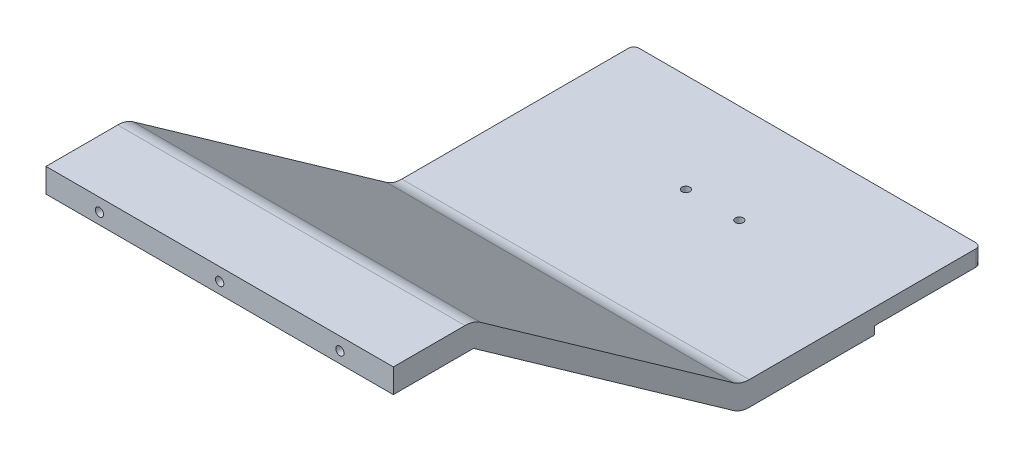
SolidWorks part; units mm, degrees
ref_plane "前视基准面" through (0, 0, 0) normal (0, 0, 1) x (1, 0, 0)
ref_plane "上视基准面" through (0, 0, 0) normal (0, 1, 0) x (1, 0, 0)
ref_plane "右视基准面" through (0, 0, 0) normal (1, 0, 0) x (0, 0, -1)
other "Configuration Table"
sketch "草图1" plane through (0, 0, 0) normal (0, 0, 1) x (1, 0, 0)
  line L0 (0, 0) -> (0, 79)
  line L1 (0, 79) -> (79, 79)
  line L2 (79, 79) -> (79, 70)
  line L3 (79, 70) -> (9, 70)
  line L4 (9, 70) -> (9, 0)
  line L5 (9, 0) -> (0, 0)
  dimension "D1" = 9
  dimension "D2" = 9
  dimension "D3" = 70
  dimension "D4" = 70
ref_plane "基准面1" through (0, 0, 100) normal (0, 0, 1) x (1, 0, 0)
sketch "草图2" plane through (0, 0, 100) normal (0, 0, 1) x (1, 0, 0)
  line L0 (0, 79) -> (-70.7107, 149.7107) construction
  line L1 (0, 0) -> (0, 79) construction
  line L2 (-70.7107, 149.7107) -> (-70.7107, 0)
  line L3 (-70.7107, 0) -> (-61.7107, 0)
  line L4 (-61.7107, 0) -> (-61.7107, 140.7107)
  line L5 (-61.7107, 140.7107) -> (79, 140.7107)
  line L6 (79, 140.7107) -> (79, 149.7107)
  line L7 (79, 149.7107) -> (-70.7107, 149.7107)
  line L8 (0, 0) -> (0, 79) construction
  line L9 (0, 79) -> (79, 79) construction
  dimension "D1" = 135
  dimension "D2" = 9
  dimension "D3" = 100
  dimension "D4" = 79
loft "放样1" add profiles "草图1", "草图2"
sketch "草图4" plane through (0, 0, 0) normal (0, 0, -1) x (-1, 0, 0)
  line L7 (-9, 0) -> (0, 0)
  line L8 (0, 0) -> (0, 79)
  line L9 (0, 79) -> (-79, 79)
  line L10 (-79, 79) -> (-79, 70)
  line L11 (-79, 70) -> (-77.7656, 70)
  line L12 (-77.7656, 70) -> (-9, 70)
  line L13 (-9, 70) -> (-9, 0)
  line L14 (-9, 0) -> (0, 0)
  line L15 (0, 0) -> (0, 79)
  line L16 (0, 79) -> (-79, 79)
  line L17 (-79, 79) -> (-79, 70)
  line L18 (-79, 70) -> (-77.7656, 70)
  line L19 (-77.7656, 70) -> (-9, 70)
  line L20 (-9, 70) -> (-9, 0)
  dimension "D1" = 0
extrude "凸台-拉伸1" add sketch "草图4" along normal blind 50
sketch "草图9" plane through (0, 0, -50) normal (0, 0, -1) x (-1, 0, 0)
  line L0 (-9, 70) -> (-9, 0) construction
  line L1 (-9, 70) -> (-55, 70)
  line L2 (-9, 70) -> (-9, 30)
  line L3 (-15, 64) -> (-55, 64)
  line L4 (-55, 70) -> (-55, 64)
  line L6 (-15, 64) -> (-15, 30)
  line L7 (-15, 30) -> (-9, 30)
  dimension "D1" = 6
  dimension "D2" = 46
  dimension "D3" = 6
  dimension "D4" = 40
extrude "凸台-拉伸3" add sketch "草图9" against normal blind 6
fillet "圆角1" radius 10 7 edges
sketch "草图11" plane through (0, 0, -44) normal (0, 0, 1) x (1, 0, 0)
  circle A0 centre (12, 45) radius 1.55
  circle A1 centre (12, 65) radius 1.55
  circle A2 centre (30, 67) radius 1.55
  circle A3 centre (50, 67) radius 1.55
  dimension "D1" = 3.1
extrude "切除-拉伸1" cut sketch "草图11" against normal through all
sketch "草图12" plane through (0, 0, -50) normal (0, 0, -1) x (-1, 0, 0)
  line L0 (0, 19) -> (0, 0)
  line L1 (0, 0) -> (0, 69) construction
  line L2 (0, 0) -> (-6, 0)
  line L3 (-9, 0) -> (0, 0) construction
  line L5 (-6, 0) -> (-6, 19)
  line L6 (0, 19) -> (-6, 19)
  line L7 (-2.9289, 76.0711) -> (-93.7798, -14.7798) construction
  line L8 (0, 0) -> (0, 69) construction
  line L9 (-60, 79) -> (-60, 73)
  line L10 (-79, 73) -> (-60, 73)
  line L11 (-79, 79) -> (-79, 73)
  line L12 (-60, 79) -> (-79, 79)
  arc A0 (0, 69) -> (-10, 79) centre (-10, 69) ccw construction
  dimension "D1" = 19
  dimension "D2" = 6
  dimension "D3" = 45
extrude "凸台-拉伸4" add sketch "草图12" along normal blind 40
fillet "圆角2" radius 2 9 edges at (3, 0, -90) (3, 19, -90) (9, 30, -47) (15, 30, -47) (15, 64, -47) (55, 70, -47) (55, 64, -47) (79, 76, -90) (60, 76, -90)
sketch "草图13" plane through (79, 0, 0) normal (1, 0, 0) x (0, 0, -1)
  line L0 (90, 79) -> (88, 79) construction
  line L1 (90, 79) -> (90, 73) construction
  line L9 (50, 73) -> (88, 73)
  line L10 (88, 73) -> (88, 79)
  line L11 (88, 79) -> (3.1784, 79)
  line L12 (-2.5951, 80.835) -> (-100, 149.7107)
  line L13 (-100, 149.7107) -> (-100, 149.2162)
  line L14 (-100, 149.2162) -> (-100, 140.7107)
  line L15 (-100, 140.7107) -> (-2.5951, 71.835)
  line L16 (3.1784, 70) -> (50, 70)
  line L17 (50, 70) -> (50, 73)
  line L18 (50, 73) -> (90, 73)
  line L19 (90, 73) -> (90, 79)
  line L20 (90, 79) -> (3.1784, 79)
  line L21 (-2.5951, 80.835) -> (-100, 149.7107)
  line L22 (-100, 149.7107) -> (-100, 149.2162)
  line L23 (-100, 149.2162) -> (-100, 140.7107)
  line L24 (-100, 140.7107) -> (-2.5951, 71.835)
  line L25 (3.1784, 70) -> (50, 70)
  line L26 (50, 70) -> (50, 73)
  arc A2 (-2.5951, 80.835) -> (3.1784, 79) centre (3.1784, 89) ccw
  arc A3 (-2.5951, 71.835) -> (3.1784, 70) centre (3.1784, 80) ccw
  arc A4 (-2.5951, 80.835) -> (3.1784, 79) centre (3.1784, 89) ccw
  arc A5 (-2.5951, 71.835) -> (3.1784, 70) centre (3.1784, 80) ccw
  dimension "D1" = 0
extrude "凸台-拉伸5" add sketch "草图13" along normal blind 130 separate body
delete or keep bodies "实体-删除/保留 1" type delete bodies bodies 112
sketch "草图14" plane through (0, 0, 100) normal (0, 0, 1) x (1, 0, 0)
  line L4 (79, 149.7107) -> (79, 140.7107)
  line L5 (79, 140.7107) -> (209, 140.7107)
  line L6 (209, 140.7107) -> (209, 149.7107)
  line L7 (209, 149.7107) -> (79, 149.7107)
  line L8 (79, 149.7107) -> (79, 140.7107)
  line L9 (79, 140.7107) -> (209, 140.7107)
  line L10 (209, 140.7107) -> (209, 149.7107)
  line L11 (209, 149.7107) -> (79, 149.7107)
  dimension "D1" = 0
extrude "凸台-拉伸6" add sketch "草图14" along normal blind 30
sketch "草图15" plane through (0, 0, 130) normal (0, 0, 1) x (1, 0, 0)
  line L0 (79, 149.7107) -> (79, 140.7107) construction
  line L1 (79, 140.7107) -> (209, 140.7107) construction
  circle A0 centre (99, 144.8907) radius 1.55
  circle A1 centre (144, 144.8907) radius 1.55
  circle A2 centre (189, 144.8907) radius 1.55
  dimension "D1" = 3.1
  dimension "D2" = 20
  dimension "D3" = 4.18
  dimension "D5" = 45
  dimension "D4" = 3
extrude "切除-拉伸2" cut sketch "草图15" against normal blind 5
fillet "圆角3" radius 2 2 edges at (79, 76, -90) (209, 76, -90)
sketch "草图16" plane through (0, 73, 0) normal (0, -1, 0) x (1, 0, 0)
  line L1 (144, 130) -> (144, 82.7932) construction
  line L2 (79, 130) -> (209, 130) construction
  line L3 (209, -50) -> (79, -50) construction
  circle A1 centre (155.5, -53) radius 1.5
  circle A2 centre (135.5, -53) radius 1.5
  dimension "D1" = 3
  dimension "D2" = 3
  dimension "D3" = 11.5
  dimension "D4" = 20
extrude "切除-拉伸3" cut sketch "草图16" against normal through all
fillet "圆角4" radius 10 1 edges at (144, 149.7107, 100)
